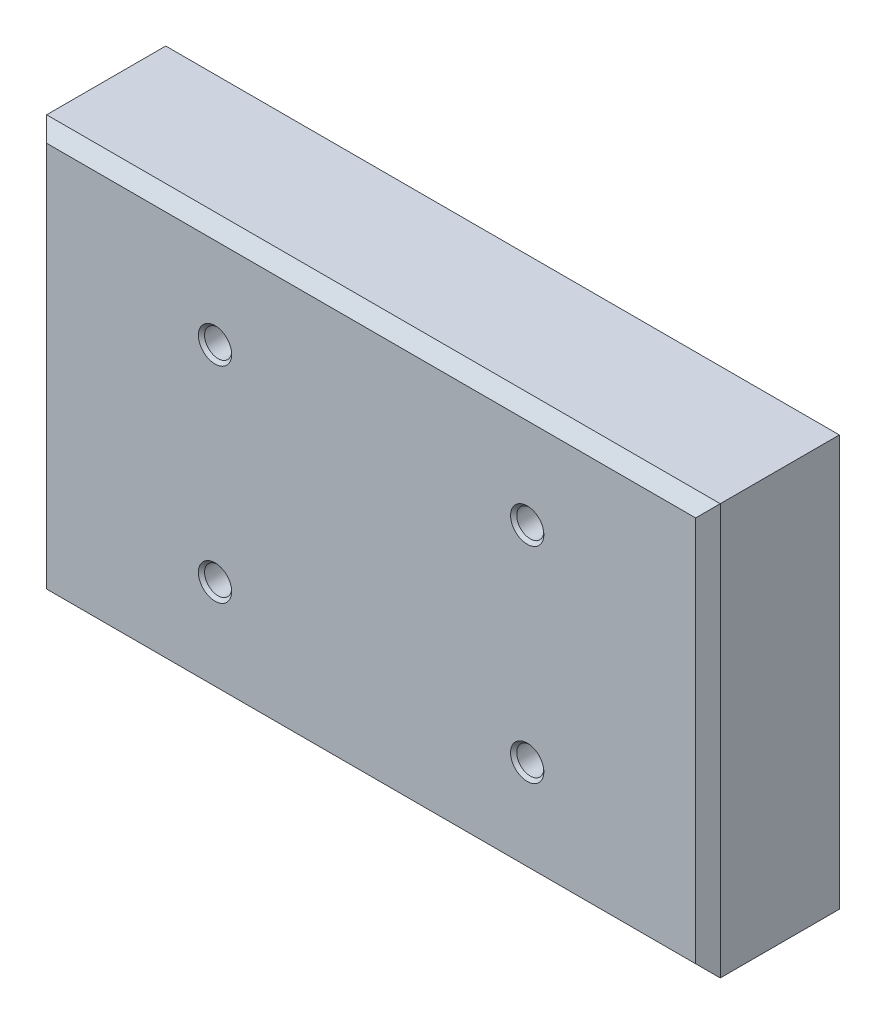
SolidWorks part; units mm, degrees
ref_plane "Ön Düzlem" through (0, 0, 0) normal (0, 0, 1) x (1, 0, 0)
ref_plane "Üst Düzlem" through (0, 0, 0) normal (0, 1, 0) x (1, 0, 0)
ref_plane "Sağ Düzlem" through (0, 0, 0) normal (1, 0, 0) x (0, 0, -1)
sketch "Sketch1" plane through (0, 0, 0) normal (0, 0, 1) x (1, 0, 0)
  line L5 (0, 0) -> (-82, 0)
  line L6 (0, 0) -> (0, 50)
  line L7 (0, 50) -> (-82, 50)
  line L8 (-82, 0) -> (-82, 50)
  dimension "D1" = 82
  dimension "D2" = 50
extrude "Boss-Extrude4" add sketch "Sketch1" along normal blind 16
hole_wizard "M4 Tapped Hole1" positions "Sketch3" profile "Sketch4" tap size "M4" standard "DIN"
sketch "Sketch3" plane through (0, 0, 16) normal (0, 0, 1) x (1, 0, 0)
  line L1 (-41, 50) -> (-41, 0) construction
  line L2 (0, 50) -> (-82, 50) construction
  line L3 (-82, 0) -> (0, 0) construction
  line L6 (-82, 25) -> (0, 25) construction
  line L7 (-82, 50) -> (-82, 0) construction
  line L8 (0, 0) -> (0, 50) construction
  point P0 (-60, 37.5)
  point P2 (-60, 12.5)
  point P4 (-22, 12.5)
  point P6 (-22, 37.5)
  dimension "D1" = 38
  dimension "D2" = 25
sketch "Sketch4" plane through (-60, 37.5, 16) normal (1, 0, 0) x (0, -1, 0)
  line L0 (0, 0) -> (0, 8.9914)
  line L1 (0, 8.9914) -> (1.65, 8)
  line L2 (1.65, 8) -> (1.65, 0.375)
  line L3 (1.65, 0.375) -> (2.025, 0)
  line L5 (2.025, 0) -> (0, 0)
  line L6 (-1.65, 0.375) -> (-2.025, 0) construction
  line L10 (0, 8.9914) -> (-1.65, 8) construction
  line L11 (0, -6.35) -> (0, 107.95) construction
  dimension "Tap Drill Dia." = 3.3
  dimension "Tap Drill Depth" = 8
  dimension "Near C'Sink Dia." = 4.05
  dimension "Near C'Sink Angle" = 90
  dimension "Drill Angle" = 118
cosmetic thread "Hole Thread1" parameters "D1"=6, "D2"=4
cosmetic thread "Hole Thread2" parameters "D1"=6, "D2"=4
cosmetic thread "Hole Thread3" parameters "D1"=6, "D2"=4
cosmetic thread "Hole Thread4" parameters "D1"=6, "D2"=4
chamfer "Chamfer1" distance 1.5 angle 45 4 edges at (-41, 50, 16) (0, 25, 16) (-41, 0, 16) (-82, 25, 16)
scale "Scale1" scale about centroid uniform scaling yes scale factor 1.5
